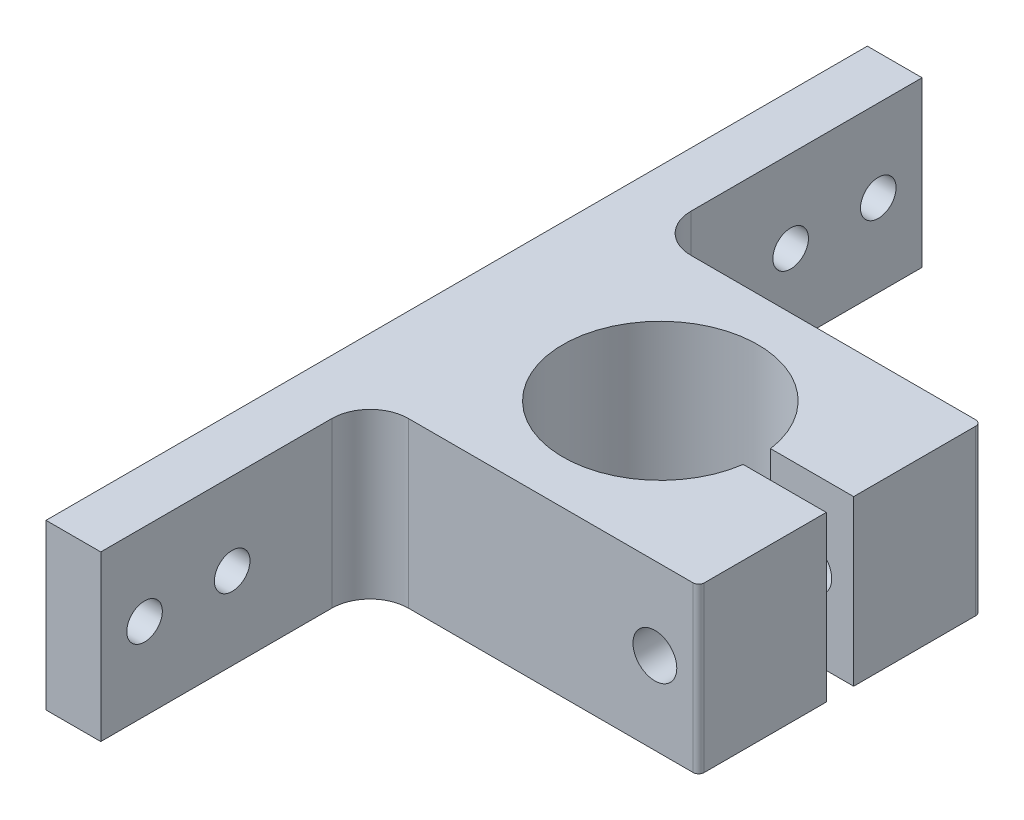
SolidWorks part; units mm, degrees
ref_plane "Front Plane" through (0, 0, 0) normal (0, 0, 1) x (1, 0, 0)
ref_plane "Top Plane" through (0, 0, 0) normal (0, 1, 0) x (1, 0, 0)
ref_plane "Right Plane" through (0, 0, 0) normal (1, 0, 0) x (0, 0, -1)
sketch "Sketch1" plane through (0, 0, 0) normal (0, 1, 0) x (1, 0, 0)
  line L1 (-35, 17.5) -> (35, 17.5)
  line L2 (-35, 17.5) -> (-35, -17.5)
  line L3 (-35, -17.5) -> (35, -17.5)
  line L4 (35, 17.5) -> (35, -17.5)
  line L5 (-35, 17.5) -> (35, -17.5) construction
  line L6 (-35, -17.5) -> (35, 17.5) construction
  point P0 (0, 0)
  dimension "D1" = 35
  dimension "D2" = 70
sketch "Sketch4" plane through (0, 0, 0) normal (0, 1, 0) x (1, 0, 0)
  line L0 (0, 75) -> (10, 75)
  line L2 (0, 75) -> (0, -75)
  line L5 (10, 75) -> (10, 25.8)
  line L6 (10, 25.8) -> (70, 25.8)
  line L7 (70, 25.8) -> (70, -25.8)
  line L8 (70, -25.8) -> (10, -25.8)
  line L9 (10, -25.8) -> (10, -75)
  line L10 (10, -75) -> (0, -75)
  line L12 (55, 0) -> (70, 0) construction
  line L13 (37.2, 17.8) -> (37.2, 25.8) construction
  line L14 (37.2, -17.8) -> (37.2, -25.8) construction
  circle A1 centre (37.2, 0) radius 17.8
  point P0 (0, 0)
  point P9 (0, 0)
  dimension "D5" = 15
  dimension "D7" = 35.6
  dimension "D1" = 70
  dimension "D2" = 150
  dimension "D3" = 10
  dimension "D4" = 10
  dimension "D6" = 8
extrude "Boss-Extrude2" add sketch "Sketch4" along normal blind 30
sketch "Sketch6" plane through (0, 30, 0) normal (0, 1, 0) x (1, 0, 0)
  line L0 (70, -25.8) -> (70, 25.8) construction
  line L1 (48.9635, -2.5) -> (70, -2.5)
  line L2 (48.9635, -2.5) -> (48.9635, 2.5)
  line L3 (48.9635, 2.5) -> (70, 2.5)
  line L4 (70, -2.5) -> (70, 2.5)
  line L5 (48.9635, -2.5) -> (70, 2.5) construction
  line L6 (48.9635, 2.5) -> (70, -2.5) construction
  line L7 (0, 0) -> (59.4817, 0) construction
  line L8 (10, -25.8) -> (70, -25.8) construction
  point P0 (59.4817, 0)
  dimension "D1" = 5
extrude "Cut-Extrude3" cut sketch "Sketch6" against normal through all
sketch "Sketch7" plane through (0, 0, 25.8) normal (0, 0, 1) x (1, 0, 0)
  line L0 (70, 15) -> (62, 15) construction
  line L1 (70, 30) -> (70, 0) construction
  circle A0 centre (62, 15) radius 4
  dimension "D1" = 8
  dimension "D2" = 8
extrude "Kiristysruuvi M8" cut sketch "Sketch7" against normal through all
sketch "Sketch9" plane through (10, 0, 0) normal (1, 0, 0) x (0, 0, -1)
  line L0 (-75, 15) -> (-25.8, 15) construction
  line L1 (-75, 30) -> (-75, 0) construction
  line L2 (-25.8, 30) -> (-25.8, 0) construction
  line L3 (0, 30) -> (0, 0) construction
  line L4 (17.8, 30) -> (-17.8, 30) construction
  circle A0 centre (-67, 15) radius 3.25
  circle A1 centre (-51, 15) radius 3.25
  circle A2 centre (67, 15) radius 3.25
  circle A3 centre (51, 15) radius 3.25
  dimension "D1" = 8
  dimension "D2" = 16
extrude "Profiiln kiinnitysreiät M6" cut sketch "Sketch9" against normal through all
fillet "Fillet1" radius 7 2 edges at (10, 15, -25.8) (10, 15, 25.8)
fillet "Fillet2" radius 1 2 edges at (70, 15, -25.8) (70, 15, 25.8)
